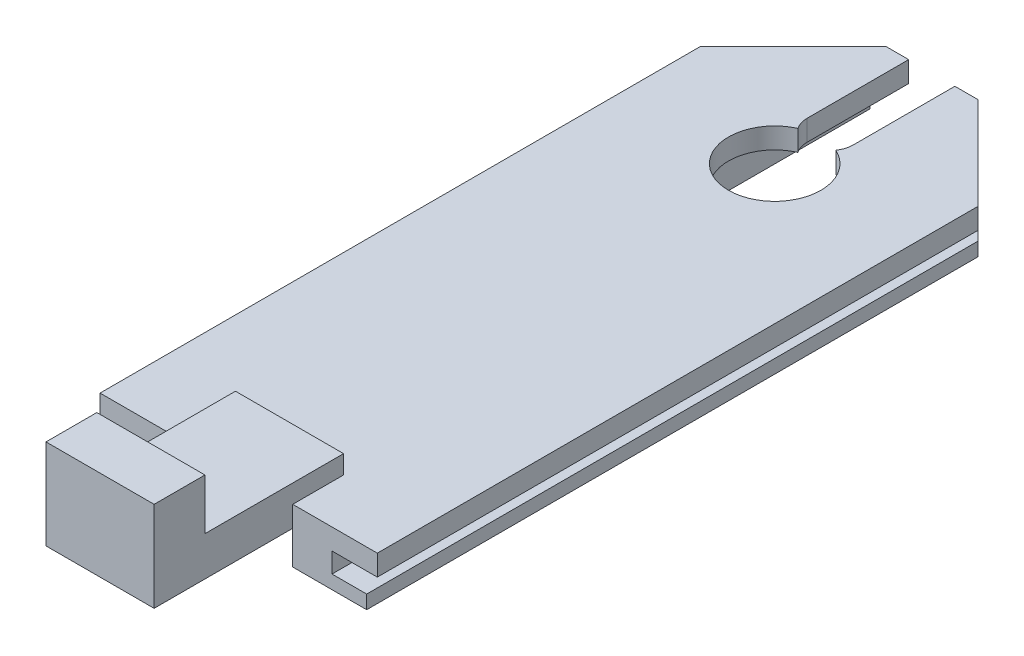
SolidWorks part; units mm, degrees
ref_plane "Front Plane" through (0, 0, 0) normal (0, 0, 1) x (1, 0, 0)
ref_plane "Top Plane" through (0, 0, 0) normal (0, 1, 0) x (1, 0, 0)
ref_plane "Right Plane" through (0, 0, 0) normal (1, 0, 0) x (0, 0, -1)
sketch "Sketch1" plane through (0, 0, 0) normal (0, 0, 1) x (1, 0, 0)
  line L0 (-15, 0) -> (15, 0)
  line L1 (15, 0) -> (15, -2.25)
  line L2 (15, -2.25) -> (10.1, -2.25)
  line L3 (10.1, -2.25) -> (10.1, -4.41)
  line L4 (10.1, -4.41) -> (13.85, -4.41)
  line L5 (13.85, -4.41) -> (13.85, -5.88)
  line L7 (5.85, -5.88) -> (5.85, -2.25)
  line L8 (5.85, -2.25) -> (-5.85, -2.25)
  line L9 (0, 0) -> (0, -2.25) construction
  line L10 (-15, 0) -> (-15, -2.25)
  line L11 (-15, -2.25) -> (-10.1, -2.25)
  line L12 (-10.1, -4.41) -> (-13.85, -4.41)
  line L13 (-13.85, -4.41) -> (-13.85, -5.88)
  line L14 (-13.85, -5.88) -> (-5.85, -5.88)
  line L15 (-5.85, -5.88) -> (-5.85, -2.25)
  line L16 (-10.1, -2.25) -> (-10.1, -4.41)
  line L17 (13.85, -5.88) -> (5.85, -5.88)
  dimension "D1" = 11.7
  dimension "D2" = 2.25
  dimension "D3" = 3.75
  dimension "D4" = 15
  dimension "D5" = 8
  dimension "D6" = 2.16
  dimension "D7" = 2.25
  dimension "D8" = 3.63
extrude "Boss-Extrude1" add sketch "Sketch1" along normal blind 75
sketch "Sketch2" plane through (0, 0, 0) normal (0, 1, 0) x (1, 0, 0)
  line L0 (0, 0) -> (0, -75) construction
  line L1 (15, -75) -> (-15, -75) construction
  line L2 (2.5, -11) -> (2.5, 0)
  line L3 (15, 0) -> (-15, 0) construction
  line L4 (2.5, 0) -> (-2.5, 0)
  line L5 (-2.5, 0) -> (-2.5, -11)
  arc A0 (-2.5, -11) -> (2.5, -11) centre (0, -11) ccw
  dimension "D1" = 11
extrude "Cut-Extrude1" cut sketch "Sketch2" against normal up to surface (2.25 mm away) up to face at (0, -2.25, 37.5)
sketch "Sketch3" plane through (0, 0, 75) normal (0, 0, 1) x (1, 0, 0)
  line L0 (15, 0) -> (-15, 0) construction
  line L1 (-5.85, -2.25) -> (5.85, -2.25)
  line L2 (-5.85, -2.25) -> (-5.85, 0)
  line L3 (-5.85, 0) -> (5.85, 0)
  line L4 (5.85, -2.25) -> (5.85, 0)
  line L5 (5.85, -2.25) -> (5.85, -5.88) construction
  dimension "D1" = 0
extrude "Boss-Extrude2" add sketch "Sketch3" along normal blind 15
sketch "Sketch4" plane through (0, 0, 0) normal (0, 1, 0) x (1, 0, 0)
  line L0 (5.85, -90) -> (5.85, -75) construction
  line L1 (-5.85, -90) -> (5.85, -90)
  line L2 (-5.85, -90) -> (-5.85, -84.5)
  line L3 (-5.85, -84.5) -> (5.85, -84.5)
  line L4 (5.85, -90) -> (5.85, -84.5)
  dimension "D1" = 5.5
extrude "Boss-Extrude3" add sketch "Sketch4" along normal blind 7.5
sketch "Sketch5" plane through (0, 0, 84.5) normal (0, 0, -1) x (-1, 0, 0)
  line L0 (5.85, 7.5) -> (5.85, 0) construction
  line L1 (-5.85, 0) -> (5.85, 0)
  line L2 (-5.85, 0) -> (-5.85, 2)
  line L3 (-5.85, 2) -> (5.85, 2)
  line L4 (5.85, 0) -> (5.85, 2)
  dimension "D1" = 2
extrude "Boss-Extrude4" add sketch "Sketch5" along normal blind 15
sketch "Sketch6" plane through (0, 0, 0) normal (0, 1, 0) x (1, 0, 0)
  circle A0 centre (0, -17) radius 5
  arc A1 (-2.5, -11) -> (2.5, -11) centre (0, -11) ccw construction
  dimension "D1" = 6
extrude "Cut-Extrude2" cut sketch "Sketch6" against normal up to surface (2.25 mm away) up to face at (0, -2.25, 35.45)
chamfer "Chamfer1" distance 10 angle 45 1 edges at (15, -1.125, 0)
chamfer "Chamfer2" distance 10 angle 45 1 edges at (-15, -1.125, 0)
